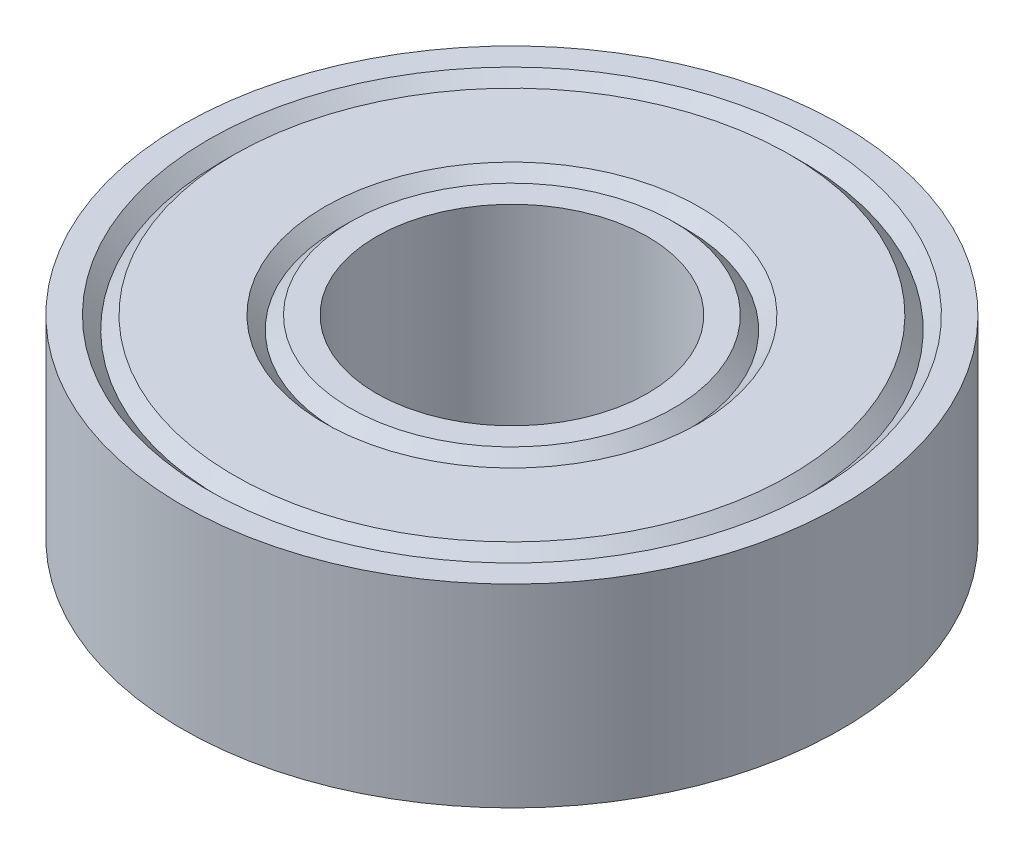
SolidWorks part; units mm, degrees
ref_plane "Front Plane" through (0, 0, 0) normal (0, 0, 1) x (1, 0, 0)
ref_plane "Top Plane" through (0, 0, 0) normal (0, 1, 0) x (1, 0, 0)
ref_plane "Right Plane" through (0, 0, 0) normal (1, 0, 0) x (0, 0, -1)
sketch "Sketch1" plane through (0, 0, 0) normal (0, 0, 1) x (1, 0, 0)
  line L0 (0, 2.5) -> (0, -2.5) construction
  line L1 (-3.5, 2.5) -> (-4.1667, 2.5)
  line L2 (-3.5, 2.5) -> (-3.5, -2.5)
  line L3 (-3.5, -2.5) -> (-4.1667, -2.5)
  line L4 (-8.5, 2.5) -> (-8.5, -2.5)
  line L5 (-7.8333, 2.5) -> (-7.5, 2.1667)
  line L6 (-7.5, 2.1667) -> (-7.1667, 2.5)
  line L7 (-4.8333, 2.5) -> (-4.5, 2.1667)
  line L8 (-4.5, 2.1667) -> (-4.1667, 2.5)
  line L9 (-7.8333, -2.5) -> (-7.5, -2.1667)
  line L10 (-7.5, -2.1667) -> (-7.1667, -2.5)
  line L11 (-4.8333, -2.5) -> (-4.5, -2.1667)
  line L12 (-4.5, -2.1667) -> (-4.1667, -2.5)
  line L13 (-4.8333, -2.5) -> (-7.1667, -2.5)
  line L14 (-7.8333, -2.5) -> (-8.5, -2.5)
  line L15 (-7.8333, 2.5) -> (-8.5, 2.5)
  line L16 (-4.8333, 2.5) -> (-7.1667, 2.5)
  line L17 (-7.5, 2.1667) -> (-4.5, 2.1667) construction
  line L18 (-7.5, 2.1667) -> (-7.5, -2.1667) construction
  line L19 (-4.5, -2.1667) -> (-7.5, -2.1667) construction
  line L20 (-4.5, 2.1667) -> (-4.5, -2.1667) construction
  line L21 (-7.5, 0) -> (-6.5, 0) construction
  line L22 (-4.1667, 2.5) -> (-4.8333, 2.5) construction
  line L23 (-6.5, 0) -> (-5.5, 0) construction
  line L24 (-7.5, 0) -> (-8.5, 0) construction
  line L25 (-5.5, 0) -> (-4.5, 0) construction
  line L26 (-4.5, 0) -> (-3.5, 0) construction
  dimension "D1" = 5
  dimension "D2" = 7
  dimension "D3" = 17
revolve "Revolve1" add sketch "Sketch1" angle 360 about L0
